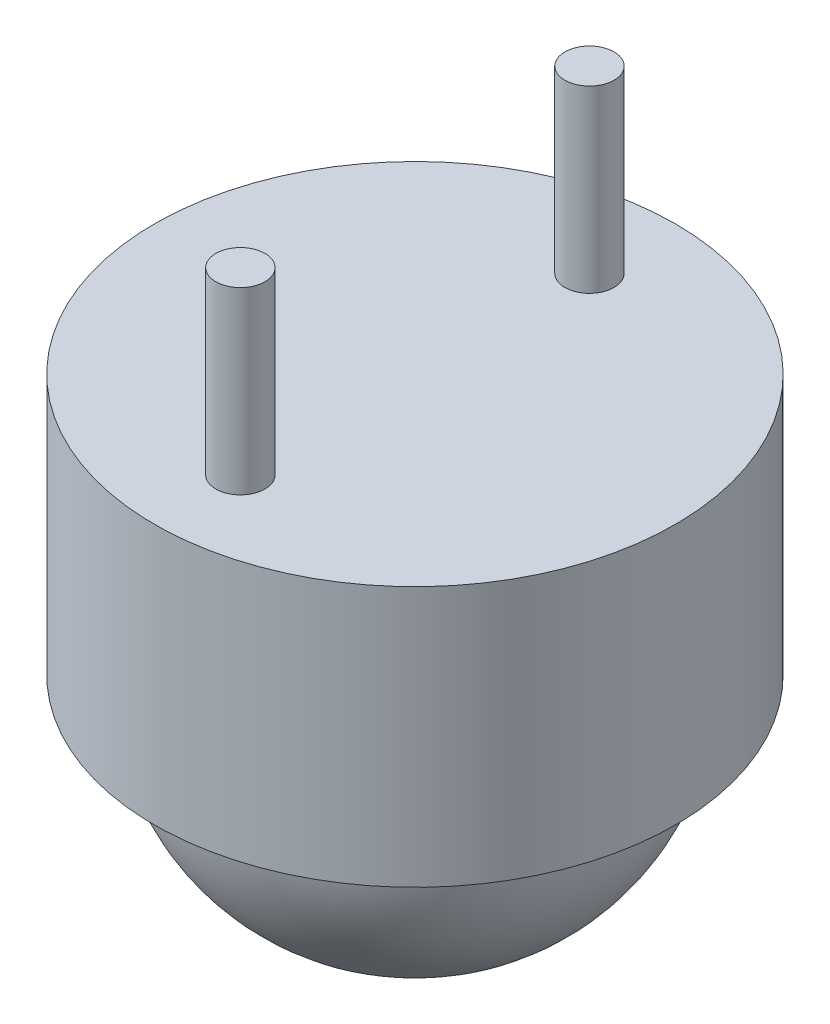
SolidWorks part; units mm, degrees
ref_plane "Front Plane" through (0, 0, 0) normal (0, 0, 1) x (1, 0, 0)
ref_plane "Top Plane" through (0, 0, 0) normal (0, 1, 0) x (1, 0, 0)
ref_plane "Right Plane" through (0, 0, 0) normal (1, 0, 0) x (0, 0, -1)
sketch "Sketch1" plane through (0, 0, 0) normal (0, 0, 1) x (1, 0, 0)
  line L0 (0, -9.525) -> (0, 9.525)
  arc A0 (0, -9.525) -> (0, 9.525) centre (0, 0) ccw
  dimension "D1" = 19.05
revolve "Metal Ball 3/4\"" add sketch "Sketch1" angle 360 about L0
sketch "Sketch2" plane through (0, 0, 0) normal (0, 1, 0) x (1, 0, 0)
  circle A0 centre (0, 0) radius 9.525
  circle A1 centre (0, 0) radius 11.557
  dimension "D1" = 2.032
extrude "Housing Pt. 1" add sketch "Sketch2" along normal blind 9.525 separate body
sketch "Sketch3" plane through (0, 9.525, 0) normal (0, 1, 0) x (1, 0, 0)
  circle A0 centre (0, 0) radius 11.557
extrude "Housing Pt. 2" add sketch "Sketch3" along normal blind 2.032
sketch "Sketch4" plane through (0, 11.557, 0) normal (0, 1, 0) x (1, 0, 0)
  line L0 (0, -7.747) -> (0, 7.747) construction
  circle A0 centre (0, 7.747) radius 1.09
  circle A1 centre (0, -7.747) radius 1.09
  point P5 (0, 0)
  dimension "D2" = 2.18
  dimension "D1" = 15.494
extrude "Screw Holes" cut sketch "Sketch4" against normal up to next (2.032 mm away)
sketch "Sketch5" plane through (0, 9.525, 0) normal (0, -1, 0) x (1, 0, 0)
  circle A0 centre (0, 7.747) radius 1.09
  circle A1 centre (0, -7.747) radius 1.09
extrude "Screws" add sketch "Sketch5" against normal blind 10 separate body
